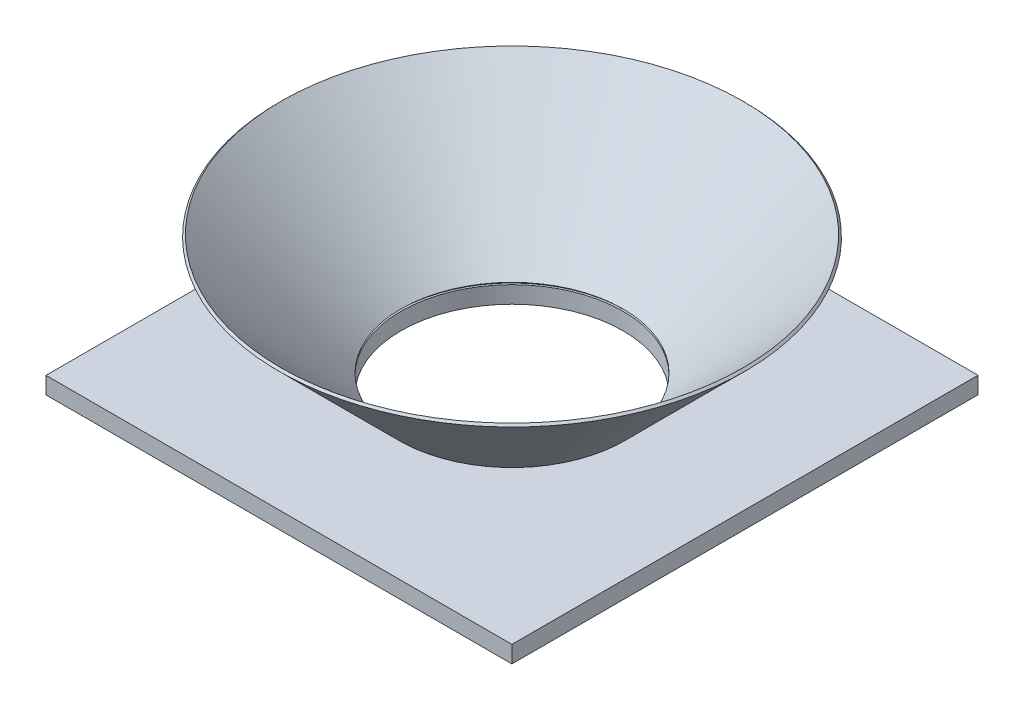
SolidWorks part; units mm, degrees
ref_plane "Front Plane" through (0, 0, 0) normal (0, 0, 1) x (1, 0, 0)
ref_plane "Top Plane" through (0, 0, 0) normal (0, 1, 0) x (1, 0, 0)
ref_plane "Right Plane" through (0, 0, 0) normal (1, 0, 0) x (0, 0, -1)
sketch "Sketch1" plane through (0, 0, 0) normal (0, 0, 1) x (1, 0, 0)
  line L0 (-20, 0) -> (-41.2132, 21.2132)
  line L1 (-41.2132, 21.2132) -> (-40.8597, 21.5668)
  line L2 (-40.8597, 21.5668) -> (-19.6464, 0.3536)
  line L3 (-19.6464, 0.3536) -> (-20, 0)
  line L4 (0, 0) -> (0, 38.049) construction
  line L5 (0, 0) -> (-37.9362, 0) construction
  dimension "D1" = 20
  dimension "D2" = 30
  dimension "D3" = 0.5
  dimension "D4" = 45
revolve "Revolve1" add sketch "Sketch1" angle 360 about L4
sketch "Sketch2" plane through (0, 0, 0) normal (0, 1, 0) x (1, 0, 0)
  line L0 (-41.2132, -41.2288) -> (41.2132, -41.2288)
  line L1 (-41.2132, -41.2288) -> (-41.2132, 41.2288)
  line L2 (41.2132, -41.2288) -> (41.2132, 41.2288)
  line L3 (-41.2132, 41.2288) -> (41.2132, 41.2288)
  line L4 (-41.2132, -41.2288) -> (41.2132, 41.2288) construction
  line L5 (41.2132, -41.2288) -> (-41.2132, 41.2288) construction
  circle A0 centre (0, 0) radius 19.6464
  point P1 (0, 0)
extrude "Boss-Extrude1" add sketch "Sketch2" against normal blind 3 separate body
